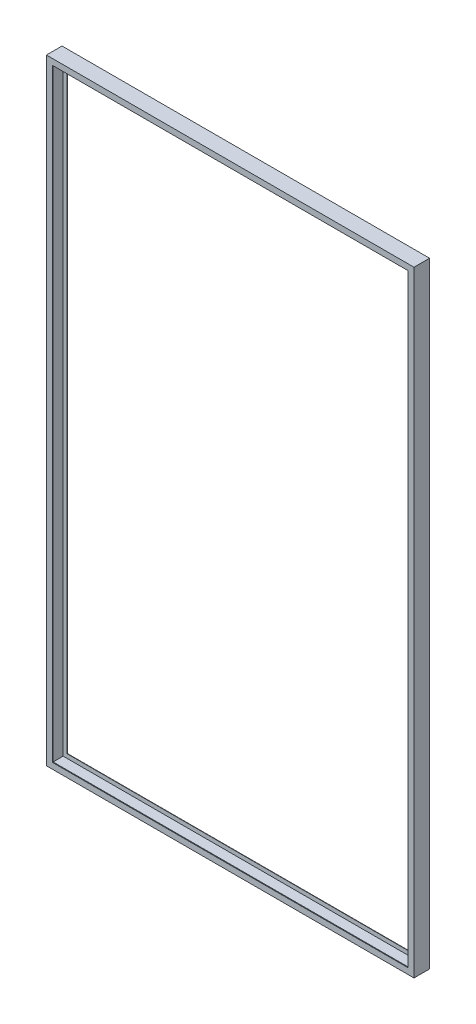
SolidWorks part; units mm, degrees
material "1060 Alloy"
ref_plane "Front Plane" through (0, 0, 0) normal (0, 0, 1) x (1, 0, 0)
ref_plane "Top Plane" through (0, 0, 0) normal (0, 1, 0) x (1, 0, 0)
ref_plane "Right Plane" through (0, 0, 0) normal (1, 0, 0) x (0, 0, -1)
sketch "Sketch1" plane through (0, 0, 0) normal (0, 0, 1) x (1, 0, 0)
  line L1 (0, 0) -> (990, 0)
  line L2 (0, 0) -> (0, 1658)
  line L3 (0, 1658) -> (990, 1658)
  line L4 (990, 0) -> (990, 1658)
  dimension "D1" = 990
  dimension "D2" = 1658
extrude "Boss-Extrude1" add sketch "Sketch1" along normal blind 42
sketch "Sketch2" plane through (0, 0, 42) normal (0, 0, 1) x (1, 0, 0)
  line L14 (16, 16) -> (974, 16)
  line L15 (974, 16) -> (974, 1642)
  line L16 (974, 1642) -> (16, 1642)
  line L17 (16, 1642) -> (16, 16)
  line L18 (16, 16) -> (974, 16)
  line L19 (974, 16) -> (974, 1642)
  line L20 (974, 1642) -> (16, 1642)
  line L21 (16, 1642) -> (16, 16)
  dimension "D1" = 16
extrude "Cut-Extrude1" cut sketch "Sketch2" against normal blind 2
sketch "Sketch3" plane through (0, 0, 40) normal (0, 0, 1) x (1, 0, 0)
  line L8 (11, 1647) -> (11, 11)
  line L9 (11, 11) -> (979, 11)
  line L10 (979, 11) -> (979, 1647)
  line L11 (979, 1647) -> (11, 1647)
  line L12 (11, 1647) -> (11, 11)
  line L13 (11, 11) -> (979, 11)
  line L14 (979, 11) -> (979, 1647)
  line L15 (979, 1647) -> (11, 1647)
  dimension "D1" = 11
extrude "Cut-Extrude2" cut sketch "Sketch3" against normal through all
ref_plane "Plane1" through (0, 0, 7) normal (0, 0, 1) x (1, 0, 0)
sketch "Sketch4" plane through (0, 0, 7) normal (0, 0, 1) x (1, 0, 0)
  line L8 (22, 1636) -> (22, 22)
  line L9 (22, 22) -> (968, 22)
  line L10 (968, 22) -> (968, 1636)
  line L11 (968, 1636) -> (22, 1636)
  line L12 (22, 1636) -> (22, 22)
  line L13 (22, 22) -> (968, 22)
  line L14 (968, 22) -> (968, 1636)
  line L15 (968, 1636) -> (22, 1636)
  line L16 (979, 1647) -> (11, 1647)
  line L17 (11, 1647) -> (11, 11)
  line L18 (11, 11) -> (979, 11)
  line L19 (979, 11) -> (979, 1647)
  line L20 (979, 1647) -> (11, 1647)
  line L21 (11, 1647) -> (11, 11)
  line L22 (11, 11) -> (979, 11)
  line L23 (979, 11) -> (979, 1647)
  dimension "D1" = 22
  dimension "D2" = 0
extrude "Boss-Extrude2" add sketch "Sketch4" along normal blind 1
sketch "Sketch5" plane through (0, 0, 0) normal (0, 0, -1) x (-1, 0, 0)
  line L9 (-5, 5) -> (-5, 1653)
  line L10 (-5, 1653) -> (-985, 1653)
  line L11 (-985, 1653) -> (-985, 5)
  line L12 (-985, 5) -> (-5, 5)
  line L13 (-5, 5) -> (-5, 1653)
  line L14 (-5, 1653) -> (-985, 1653)
  line L15 (-985, 1653) -> (-985, 5)
  line L16 (-985, 5) -> (-5, 5)
  dimension "D1" = 5
extrude "Cut-Extrude3" cut sketch "Sketch5" against normal up to surface (3 mm away) from offset 4 up to face at (495, 829, 7) offset against normal yes
chamfer "Chamfer1" distance 3 angle 60 4 edges at (979, 829, 0) (495, 11, 0) (11, 829, 0) (495, 1647, 0)
